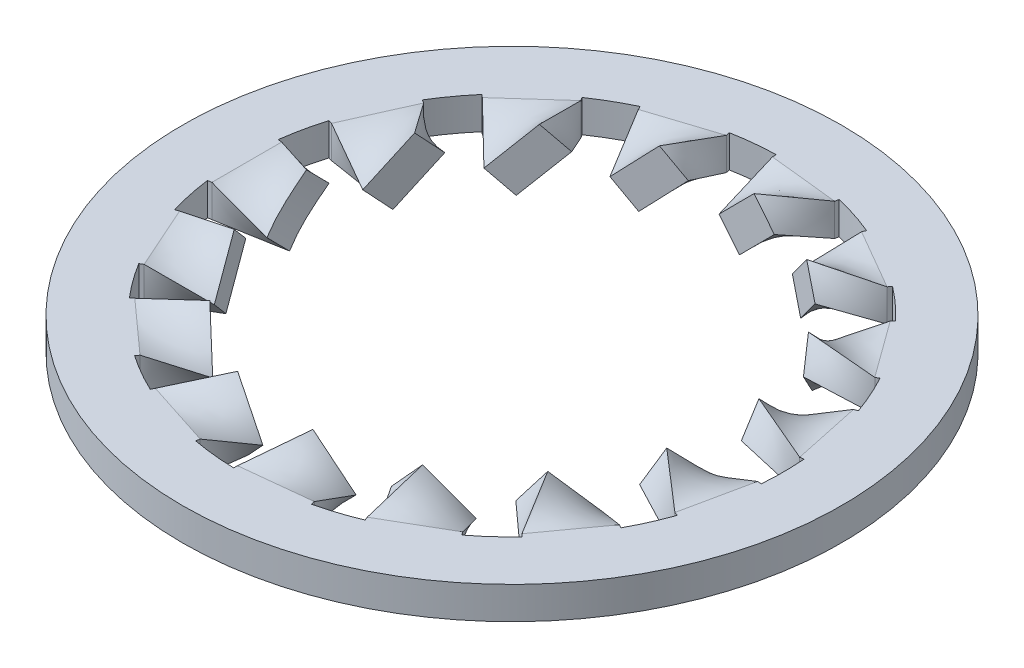
SolidWorks part; units mm, degrees
material "Brass"
ref_plane "Ön Düzlem" through (0, 0, 0) normal (0, 0, 1) x (1, 0, 0)
ref_plane "Üst Düzlem" through (0, 0, 0) normal (0, 1, 0) x (1, 0, 0)
ref_plane "Sağ Düzlem" through (0, 0, 0) normal (1, 0, 0) x (0, 0, -1)
sketch "Sketch2" plane through (0, 0, 0) normal (0, 1, 0) x (1, 0, 0)
  line L0 (-4.1046, -0.54) -> (-4.1046, 0.54)
  line L1 (-3.9694, 1.1762) -> (-3.5301, 2.1628)
  line L2 (-3.1478, 2.689) -> (-2.3452, 3.4117)
  line L3 (-1.782, 3.7369) -> (-0.7548, 4.0706)
  line L4 (-0.108, 4.1386) -> (0.9661, 4.0257)
  line L5 (1.5847, 3.8247) -> (2.52, 3.2847)
  line L6 (3.0033, 2.8495) -> (3.6381, 1.9758)
  line L7 (3.9027, 1.3816) -> (4.1272, 0.3252)
  line L8 (4.1272, -0.3252) -> (3.9027, -1.3816)
  line L9 (3.6381, -1.9758) -> (3.0033, -2.8495)
  line L10 (2.52, -3.2847) -> (1.5847, -3.8247)
  line L11 (0.9661, -4.0257) -> (-0.108, -4.1386)
  line L12 (-0.7548, -4.0706) -> (-1.782, -3.7369)
  line L13 (-2.3452, -3.4117) -> (-3.1478, -2.689)
  line L14 (-3.5301, -2.1628) -> (-3.9694, -1.1762)
  line L15 (-4.1046, 0.54) -> (-4.1641, 0.5478)
  line L16 (-3.5301, 2.1628) -> (-3.5813, 2.1942)
  line L17 (-2.3452, 3.4117) -> (-2.3792, 3.4611)
  line L18 (-0.7548, 4.0706) -> (-0.7658, 4.1296)
  line L19 (0.9661, 4.0257) -> (0.9801, 4.084)
  line L20 (2.52, 3.2847) -> (2.5565, 3.3323)
  line L21 (3.6381, 1.9758) -> (3.6908, 2.0044)
  line L22 (4.1272, 0.3252) -> (4.187, 0.3299)
  line L23 (3.9027, -1.3816) -> (3.9592, -1.4016)
  line L24 (3.0033, -2.8495) -> (3.0468, -2.8908)
  line L25 (1.5847, -3.8247) -> (1.6076, -3.8801)
  line L26 (-0.108, -4.1386) -> (-0.1096, -4.1986)
  line L27 (-1.782, -3.7369) -> (-1.8078, -3.791)
  line L28 (-3.1478, -2.689) -> (-3.1935, -2.728)
  line L29 (-3.9694, -1.1762) -> (-4.0269, -1.1932)
  line L30 (-4.1046, -0.54) -> (-4.1641, -0.5478)
  line L31 (-3.9694, 1.1762) -> (-4.0269, 1.1932)
  line L32 (-3.1478, 2.689) -> (-3.1935, 2.728)
  line L33 (-1.782, 3.7369) -> (-1.8078, 3.791)
  line L34 (-0.108, 4.1386) -> (-0.1096, 4.1986)
  line L35 (1.5847, 3.8247) -> (1.6076, 3.8801)
  line L36 (3.0033, 2.8495) -> (3.0468, 2.8908)
  line L37 (3.9027, 1.3816) -> (3.9592, 1.4016)
  line L38 (4.1272, -0.3252) -> (4.187, -0.3299)
  line L39 (3.6381, -1.9758) -> (3.6908, -2.0044)
  line L40 (2.52, -3.2847) -> (2.5565, -3.3323)
  line L41 (0.9661, -4.0257) -> (0.9801, -4.084)
  line L42 (-0.7548, -4.0706) -> (-0.7658, -4.1296)
  line L43 (-2.3452, -3.4117) -> (-2.3792, -3.4611)
  line L44 (-3.5301, -2.1628) -> (-3.5813, -2.1942)
  arc A0 (-4.0269, 1.1932) -> (-4.1641, 0.5478) centre (0, 0) ccw
  circle A2 centre (0, 0) radius 5.1
  arc A3 (-3.1935, 2.728) -> (-3.5813, 2.1942) centre (0, 0) ccw
  arc A4 (-1.8078, 3.791) -> (-2.3792, 3.4611) centre (0, 0) ccw
  arc A5 (-0.1096, 4.1986) -> (-0.7658, 4.1296) centre (0, 0) ccw
  arc A6 (1.6076, 3.8801) -> (0.9801, 4.084) centre (0, 0) ccw
  arc A7 (3.0468, 2.8908) -> (2.5565, 3.3323) centre (0, 0) ccw
  arc A8 (3.9592, 1.4016) -> (3.6908, 2.0044) centre (0, 0) ccw
  arc A9 (4.187, -0.3299) -> (4.187, 0.3299) centre (0, 0) ccw
  arc A10 (3.6908, -2.0044) -> (3.9592, -1.4016) centre (0, 0) ccw
  arc A11 (2.5565, -3.3323) -> (3.0468, -2.8908) centre (0, 0) ccw
  arc A12 (0.9801, -4.084) -> (1.6076, -3.8801) centre (0, 0) ccw
  arc A13 (-0.7658, -4.1296) -> (-0.1096, -4.1986) centre (0, 0) ccw
  arc A14 (-2.3792, -3.4611) -> (-1.8078, -3.791) centre (0, 0) ccw
  arc A16 (-3.5813, -2.1942) -> (-3.1935, -2.728) centre (0, 0) ccw
  arc A17 (-4.1641, -0.5478) -> (-4.0269, -1.1932) centre (0, 0) ccw
  point P37 (0, 0)
  point P53 (0, 0)
  point P69 (0, 0)
  dimension "D1" = 10.2
  dimension "D2" = 8.4
  dimension "D3" = 4.1046
  dimension "D4" = 4.1046
  dimension "D6" = 4.1046
  dimension "D5" = 15
extrude "Boss-Extrude1" add sketch "Sketch2" along normal mid plane 0.5
ref_plane "Plane1" through (-4.1046, 0, 0) normal (1, 0, 0) x (0, 0, -1)
ref_plane "Plane2" through (-3.3046, 0, 0) normal (1, 0, 0) x (0, 0, -1)
sketch "Sketch3" plane through (-4.1046, 0, 0) normal (1, 0, 0) x (0, 0, -1)
  line L4 (0.54, -0.25) -> (-0.54, -0.25)
  line L5 (0.54, 0.25) -> (0.54, -0.25)
  line L6 (0.54, 0.25) -> (-0.54, 0.25)
  line L7 (-0.54, 0.25) -> (-0.54, -0.25)
  point P4 (0, 0.25)
  point P7 (-0.54, 0)
  dimension "D1" = 1.08
  dimension "D2" = 0.5
  dimension "D3" = 0.25
  dimension "D4" = 0.54
sketch "Sketch6" plane through (-3.3046, 0, 0) normal (1, 0, 0) x (0, 0, -1)
  line L0 (-0.1273, -0.4808) -> (0.1273, 0.4808) construction
  line L1 (-0.4808, -0.1273) -> (0.4808, 0.1273) construction
  line L2 (0, -0.4191) -> (0, 0.7235) construction
  line L8 (-0.1273, -0.4808) -> (0.4808, 0.1273)
  line L9 (-0.4808, -0.1273) -> (-0.1273, -0.4808)
  line L10 (0.1273, 0.4808) -> (-0.4808, -0.1273)
  line L11 (0.4808, 0.1273) -> (0.1273, 0.4808)
  point P6 (0, 0)
  dimension "D1" = 0.5
  dimension "D2" = 0.86
  dimension "D3" = 45
loft "Loft3" add profiles "Sketch3", "Sketch6"
ref_plane "Plane3" through (0, 0, 0) normal (0, 0.7071, 0.7071) x (1, 0, 0)
sketch "Sketch7" plane through (0, 0, 0) normal (0, 0.7071, 0.7071) x (1, 0, 0)
  circle A0 centre (0, 0) radius 3.3394
  dimension "D1" = 6.6789
sketch "Sketch8" plane through (0, 0, 0) normal (0, 1, 0) x (1, 0, 0)
  line L4 (-3.3046, -0.4808) -> (-3.3046, 0.4808) construction
  line L7 (-3.3046, 0.4808) -> (0, 0) construction
  line L11 (0, 0) -> (-3.3046, -0.4808) construction
  dimension "D1" = 0.9617
  dimension "D2" = 0.4808
  dimension "D3" = 3.3394
extrude "Cut-Extrude2" cut sketch "Sketch7" against normal mid plane 0.6
pattern_circular "CirPattern1" count 15 over 360 about axis through (0, 0.25, 0) along (0, 1, 0) of "Loft3"
